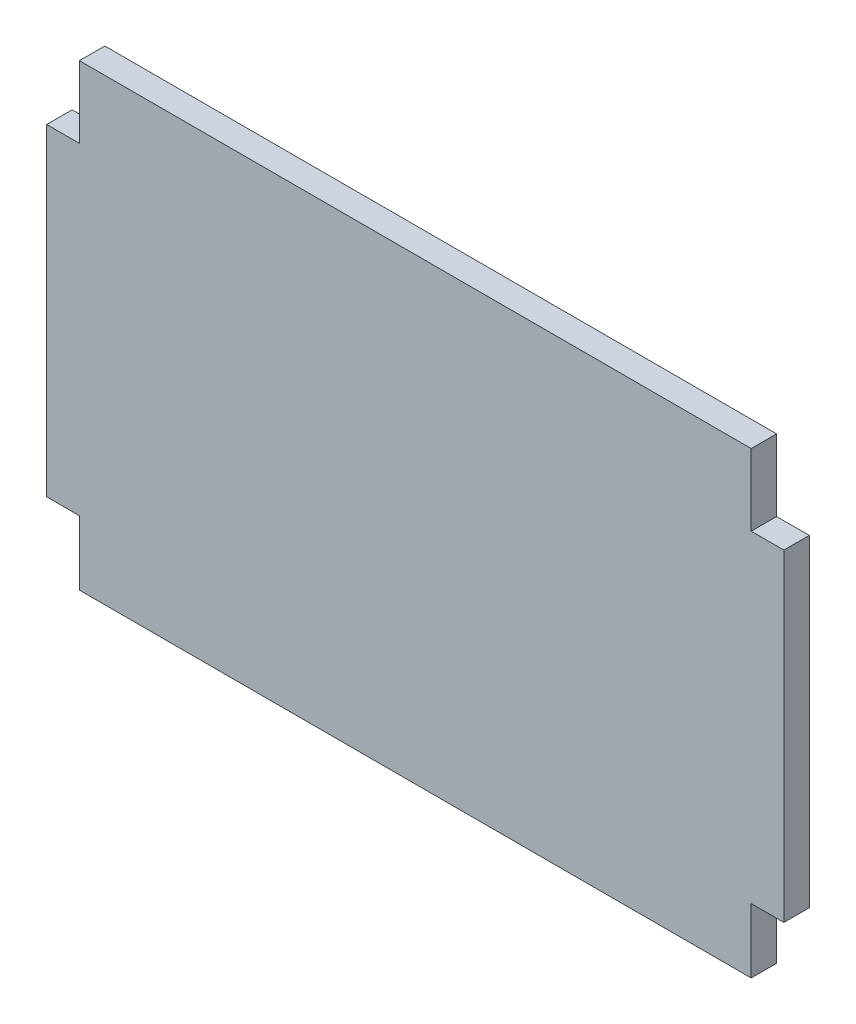
SolidWorks part; units mm, degrees
ref_plane "Front Plane" through (0, 0, 0) normal (0, 0, 1) x (1, 0, 0)
ref_plane "Top Plane" through (0, 0, 0) normal (0, 1, 0) x (1, 0, 0)
ref_plane "Right Plane" through (0, 0, 0) normal (1, 0, 0) x (0, 0, -1)
sketch "Sketch1" plane through (0, 0, 0) normal (0, 0, 1) x (1, 0, 0)
  line L1 (-79.0312, 49.1611) -> (124.1688, 49.1611)
  line L2 (-79.0312, 49.1611) -> (-79.0312, -77.2389)
  line L3 (-79.0312, -77.2389) -> (124.1688, -77.2389)
  line L4 (124.1688, 49.1611) -> (124.1688, -77.2389)
  dimension "D1" = 203.2
  dimension "D2" = 126.4
extrude "Boss-Extrude1" add sketch "Sketch1" along normal blind 7
sketch "Sketch2" plane through (0, 0, 7) normal (0, 0, 1) x (1, 0, 0)
  line L0 (22.5688, 49.1611) -> (22.5688, -77.2389) construction
  line L5 (124.1688, 49.1611) -> (-79.0312, 49.1611) construction
  line L6 (-79.0312, -77.2389) -> (124.1688, -77.2389) construction
  line L7 (124.1688, -77.2389) -> (124.1688, 49.1611) construction
  line L12 (-79.0312, -59.4765) -> (-79.0312, -77.2389)
  line L13 (-70.0312, -77.2389) -> (-79.0312, -77.2389)
  line L14 (-70.0312, -59.4765) -> (-70.0312, -77.2389)
  line L15 (115.1688, -59.4765) -> (124.1688, -59.4765)
  line L16 (115.1688, -59.4765) -> (115.1688, -77.2389)
  line L17 (115.1688, -77.2389) -> (124.1688, -77.2389)
  line L18 (124.1688, -59.4765) -> (124.1688, -77.2389)
  line L19 (115.1688, 29.4235) -> (124.1688, 29.4235)
  line L20 (115.1688, 29.4235) -> (115.1688, 49.1611)
  line L21 (115.1688, 49.1611) -> (124.1688, 49.1611)
  line L22 (124.1688, 29.4235) -> (124.1688, 49.1611)
  line L23 (-70.0312, -59.4765) -> (-79.0312, -59.4765)
  line L24 (-70.0312, 49.1611) -> (-79.0312, 49.1611)
  line L25 (-79.0312, 29.4235) -> (-79.0312, 49.1611)
  line L26 (-70.0312, 29.4235) -> (-79.0312, 29.4235)
  line L27 (-70.0312, 29.4235) -> (-70.0312, 49.1611)
  dimension "D1" = 9
  dimension "D2" = 9
  dimension "D3" = 88.9
extrude "Cut-Extrude1" cut sketch "Sketch2" against normal up to surface (7 mm away) up to face at (22.5688, -14.0389, 0)
